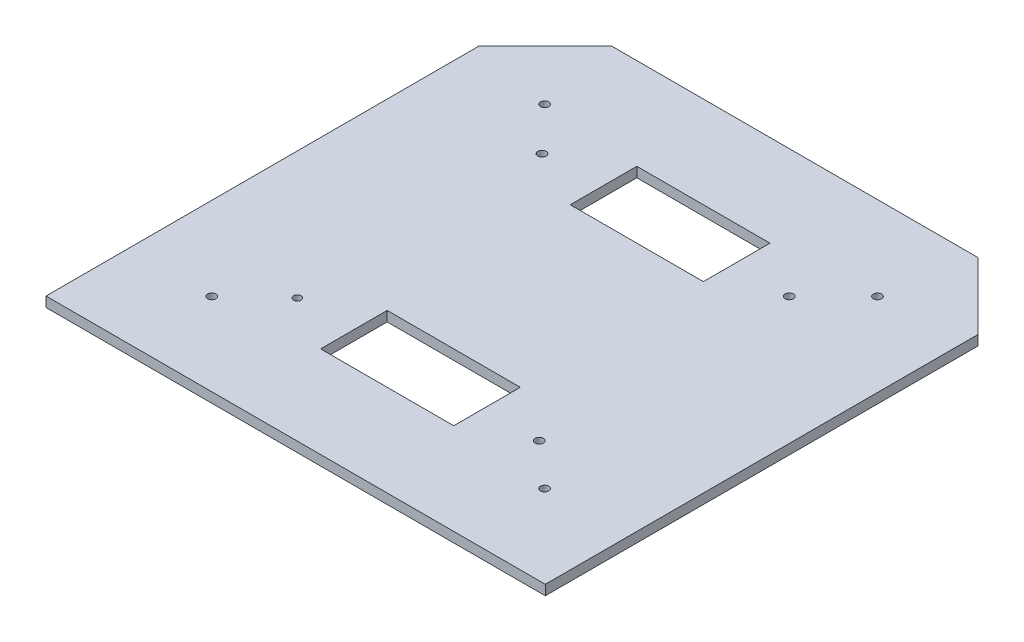
SolidWorks part; units mm, degrees
ref_plane "Plan de face" through (0, 0, 0) normal (0, 0, 1) x (1, 0, 0)
ref_plane "Plan de dessus" through (0, 0, 0) normal (0, 1, 0) x (1, 0, 0)
ref_plane "Plan de droite" through (0, 0, 0) normal (1, 0, 0) x (0, 0, -1)
sketch "Esquisse1" plane through (0, 0, 0) normal (0, 1, 0) x (1, 0, 0)
  line L0 (-150, 0) -> (-150, 260)
  line L2 (150, 0) -> (150, 260)
  line L3 (-150, 260) -> (-110, 260) construction
  line L4 (-110, 260) -> (-110, 300) construction
  line L5 (150, 260) -> (110, 260) construction
  line L6 (110, 260) -> (110, 300) construction
  line L8 (-150, 260) -> (-110, 300)
  line L9 (-110, 300) -> (110, 300)
  line L10 (0, 0) -> (0, 300) construction
  line L11 (110, 300) -> (150, 260)
  line L12 (-150, 0) -> (-120, 0) construction
  line L13 (-120, 18) -> (-120, 0) construction
  line L14 (150, 0) -> (120, 0) construction
  line L15 (120, 18) -> (120, 0) construction
  line L17 (-150, 260) -> (-120, 260) construction
  line L18 (-120, 260) -> (-120, 267.75) construction
  line L19 (150, 260) -> (120, 260) construction
  line L20 (120, 260) -> (120, 268.5) construction
  line L21 (-120, 267.75) -> (-111.5147, 276.2353) construction
  line L22 (-120, 267.75) -> (-128.4853, 259.2647) construction
  line L23 (120, 268.5) -> (128.4853, 260.0147) construction
  line L24 (120, 268.5) -> (111.5147, 276.9853) construction
  line L25 (-150, 0) -> (150, 0) construction
  line L26 (120, 30) -> (120, 18) construction
  line L27 (120, 30) -> (120, 42) construction
  line L28 (-150, 0) -> (150, 0)
  line L29 (-120, 18) -> (-120, 30) construction
  line L30 (-120, 30) -> (-120, 42) construction
  line L31 (0, 150) -> (0, 0) construction
  line L32 (150, 150) -> (-150, 150) construction
  line L33 (-120, 30) -> (-108, 30) construction
  line L34 (-120, 30) -> (-132, 30) construction
  line L35 (120, 30) -> (132, 30) construction
  line L36 (120, 30) -> (108, 30) construction
  line L37 (0, 0) -> (0, 75) construction
  line L39 (40, 75) -> (40, 55) construction
  line L40 (40, 55) -> (-40, 55)
  line L41 (-40, 55) -> (-40, 95)
  line L42 (-40, 95) -> (40, 95)
  line L43 (40, 95) -> (40, 55)
  line L44 (0, 300) -> (0, 150) construction
  line L45 (-40, 245) -> (-40, 205)
  line L47 (40, 245) -> (-40, 245)
  line L48 (-40, 205) -> (40, 205)
  line L49 (40, 205) -> (40, 245)
extrude "Boss.-Extru.1" add sketch "Esquisse1" along normal blind 6
sketch "Esquisse9" plane through (0, 6, 0) normal (0, 1, 0) x (1, 0, 0)
  line L0 (-150, 0) -> (150, 0) construction
  line L1 (150, 0) -> (150, 300) construction
  line L2 (150, 300) -> (-150, 300) construction
  line L3 (-150, 300) -> (-150, 0) construction
  line L4 (-100, 49.6023) -> (-73.4894, 74.471) construction
  line L5 (-150, 0) -> (-150, 300) construction
  line L6 (150, 0) -> (0, 0) construction
  line L7 (0, 0) -> (0, 49.6023) construction
  line L8 (0, 0) -> (0, 300) construction
  line L9 (0, 49.6023) -> (100, 49.6023) construction
  line L10 (100, 49.6023) -> (100, 249.6023) construction
  line L11 (100, 249.6023) -> (-100, 249.6023) construction
  line L12 (-100, 249.6023) -> (-100, 49.6023) construction
  line L13 (-100, 49.6023) -> (0, 49.6023) construction
  line L14 (100, 249.6023) -> (73.4835, 223.0858) construction
  line L16 (-100, 249.6023) -> (-75.0311, 223.0858) construction
  line L17 (100, 49.6023) -> (73.4835, 72.8652) construction
  circle A22 centre (100, 249.6023) radius 12.5 construction
  circle A25 centre (-100, 249.6023) radius 12.5 construction
  circle A26 centre (-100, 49.6023) radius 12.5 construction
  circle A27 centre (100.0826, 47.2131) radius 12.5 construction
  circle A30 centre (-75.0311, 223.0858) radius 10 construction
  circle A31 centre (73.4835, 223.0858) radius 10 construction
  circle A32 centre (73.4835, 72.8652) radius 10 construction
  circle A33 centre (-73.4894, 74.471) radius 10 construction
  circle A34 centre (-100, 249.6023) radius 2.5
  circle A35 centre (-75.0311, 223.0858) radius 2.5
  circle A36 centre (73.4835, 223.0858) radius 2.5
  circle A37 centre (100, 249.6023) radius 2.5
  circle A38 centre (73.4835, 72.8652) radius 2.5
  circle A39 centre (100, 49.6023) radius 2.5
  circle A40 centre (-73.4894, 74.471) radius 2.3
  circle A41 centre (-100, 49.6023) radius 2.5
  point P16 (0, 0)
  point P24 (0, 0)
  point P38 (0, 0)
extrude "Enlèv. mat.-Extru.12" cut sketch "Esquisse9" against normal blind 35
